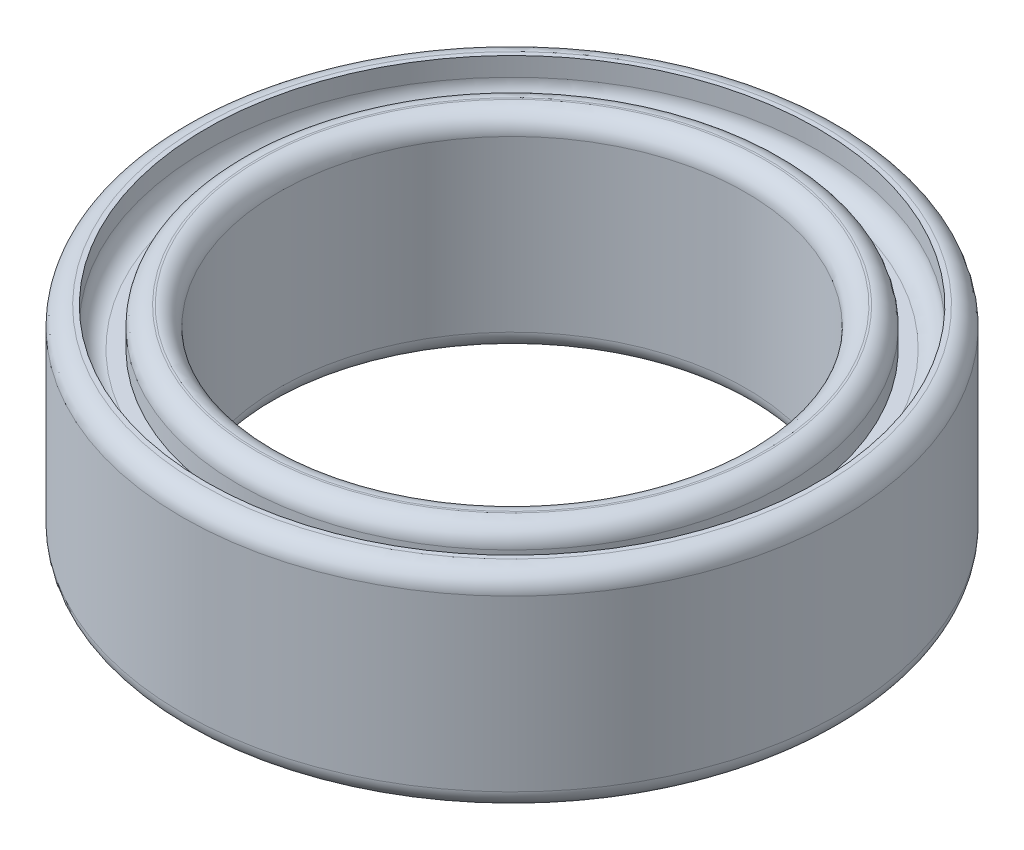
SolidWorks part; units mm, degrees
material "AISI 304"
ref_plane "Front Plane" through (0, 0, 0) normal (0, 0, 1) x (1, 0, 0)
ref_plane "Top Plane" through (0, 0, 0) normal (0, 1, 0) x (1, 0, 0)
ref_plane "Right Plane" through (0, 0, 0) normal (1, 0, 0) x (0, 0, -1)
sketch "Sketch1" plane through (0, 0, 0) normal (0, 1, 0) x (1, 0, 0)
  circle A0 centre (0, 0) radius 17.5
  circle A1 centre (0, 0) radius 12.4
  dimension "D1" = 24.8
  dimension "D2" = 35
extrude "Boss-Extrude1" add sketch "Sketch1" along normal blind 11
sketch "Sketch2" plane through (0, 11, 0) normal (0, 1, 0) x (1, 0, 0)
  circle A0 centre (0, 0) radius 16.25
  circle A1 centre (0, 0) radius 14.5
  dimension "D1" = 32.5
  dimension "D2" = 29
fillet "Fillet3" radius 1 2 edges at (0, 11, 12.4) (0, 0, 12.4)
extrude "Cut-Extrude3" cut sketch "Sketch2" against normal blind 2
sketch "Sketch4" plane through (0, 0, 0) normal (0, -1, 0) x (1, 0, 0)
  circle A0 centre (0, 0) radius 14.5
  circle A1 centre (0, 0) radius 16.25
  dimension "D1" = 32.5
extrude "Cut-Extrude4" cut sketch "Sketch4" against normal blind 2
fillet "Fillet4" radius 1 4 edges at (0, 0, -14.5) (0, 11, 14.5) (0, 11, 17.5) (0, 0, 17.5)
fillet "Fillet5" radius 1 2 edges at (0, 9, 16.25) (0, 2, -16.25)
